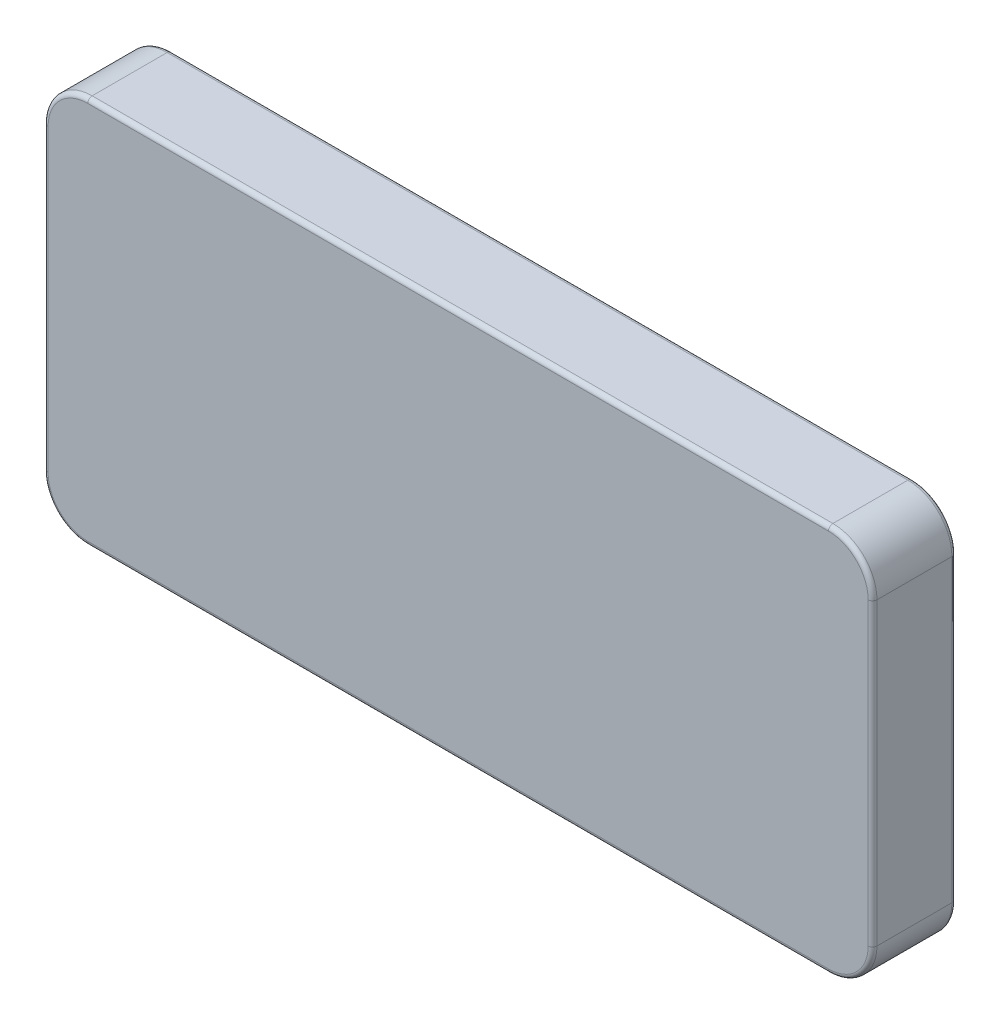
SolidWorks part; units mm, degrees
ref_plane "Plan de face" through (0, 0, 0) normal (0, 0, 1) x (1, 0, 0)
ref_plane "Plan de dessus" through (0, 0, 0) normal (0, 1, 0) x (1, 0, 0)
ref_plane "Plan de droite" through (0, 0, 0) normal (1, 0, 0) x (0, 0, -1)
sketch "Esquisse1" plane through (0, 0, 0) normal (0, 0, 1) x (1, 0, 0)
  line L1 (0, 0) -> (1880, 0)
  line L2 (0, 0) -> (0, 880)
  line L3 (0, 880) -> (1880, 880)
  line L4 (1880, 0) -> (1880, 880)
  dimension "D1" = 880
  dimension "D2" = 1880
extrude "Boss.-Extru.1" add sketch "Esquisse1" along normal blind 190
fillet "Congé1" radius 100 4 edges at (0, 880, 95) (0, 0, 95) (1880, 0, 95) (1880, 880, 95)
fillet "Congé2" radius 10 16 edges at (29.2893, 29.2893, 0) (940, 0, 0) (1850.7107, 29.2893, 0) (1880, 440, 0) (1850.7107, 850.7107, 0) (940, 880, 0) (29.2893, 850.7107, 0) (0, 440, 0) (1850.7107, 850.7107, 190) (1880, 440, 190) (1850.7107, 29.2893, 190) (940, 0, 190) (29.2893, 29.2893, 190) (0, 440, 190) (29.2893, 850.7107, 190) (940, 880, 190)
